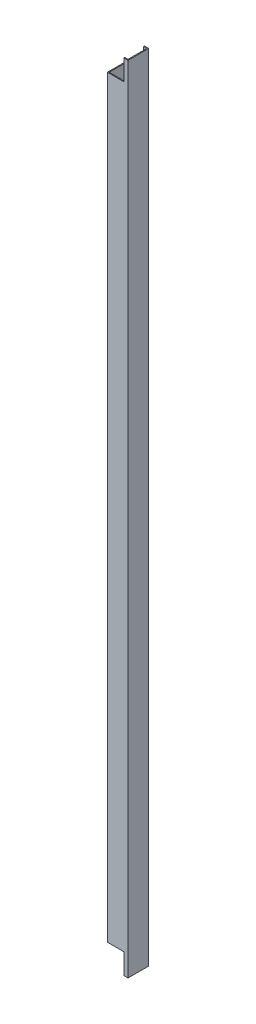
SolidWorks part; units mm, degrees
ref_plane "Front Plane" through (0, 0, 0) normal (0, 0, 1) x (1, 0, 0)
ref_plane "Top Plane" through (0, 0, 0) normal (0, 1, 0) x (1, 0, 0)
ref_plane "Right Plane" through (0, 0, 0) normal (1, 0, 0) x (0, 0, -1)
sketch "Sketch1" plane through (0, 0, 0) normal (0, 1, 0) x (1, 0, 0)
  line L0 (0, 0) -> (0, 50)
  line L1 (0, 50) -> (50, 50)
  line L2 (50, 50) -> (50, 0)
  line L3 (50, 0) -> (0, 0)
  line L4 (2.2, 47.8) -> (47.8, 47.8)
  line L5 (47.8, 47.8) -> (47.8, 2.2)
  line L6 (47.8, 2.2) -> (2.2, 2.2)
  line L7 (2.2, 2.2) -> (2.2, 47.8)
  dimension "D1" = 50
  dimension "D2" = 50
  dimension "D3" = 2.2
extrude "Boss-Extrude1" add sketch "Sketch1" along normal blind 1923
sketch "Sketch2" plane through (0, 0, 0) normal (0, 0, 1) x (1, 0, 0)
  line L0 (0, 0) -> (0, 50)
  line L1 (0, 1923) -> (0, 0) construction
  line L2 (0, 50) -> (40, 50)
  line L3 (40, 50) -> (40, 0)
  line L5 (40, 0) -> (0, 0)
  line L6 (0, 1923) -> (40, 1923)
  line L7 (0, 1923) -> (50, 1923) construction
  line L8 (40, 1923) -> (40, 1873)
  line L9 (40, 1873) -> (0, 1873)
  line L10 (0, 1873) -> (0, 1923)
  dimension "D1" = 50
  dimension "D2" = 40
  dimension "D3" = 50
  dimension "D4" = 40
extrude "Cut-Extrude2" cut sketch "Sketch2" against normal blind 50
equation "\"SquareTube_length\"=1923.0"
equation "\"D1@Boss-Extrude1\"=\"SquareTube_length\""
equation "\"SquareTube_inBack1_cutDepth50_R\"=50"
equation "\"D1@Sketch2\" = \"SquareTube_inBack5_cutDepth50_R\""
equation "\"SquareTube_inBack1_cutDepth50_L\"=50"
equation "\"D3@Sketch2\" = \"SquareTube_inBack5_cutDepth50_L\""
equation "\"CarBeamWidth\"=700.0"
equation "\"MetalSheet_3mm_length\"=5030.0"
equation "\"MetalSheet_3mm_width\"=1923.0"
equation "\"MetalSheet_3mm_FloorCut_L_length\"=1764.0"
equation "\"MetalSheet_3mm_FloorCut_L_disdance\"=1665.0"
equation "\"MetalSheet_3mm_FloorCut_R_length\"=1764.0"
equation "\"MetalSheet_3mm_FloorCut_R_disdance\"=1665.0"
equation "\"indoorHeight\"=1940.0"
equation "\"x\"=66.0"
equation "\"da\"=62.0"
equation "\"SquareTube_wheel_length\"= 750"
equation "\"channelSteel_length\"=5030.0"
equation "\"SquareTube_inFront1_cutDepth50_R\"=0.5"
equation "\"SquareTube_inFront1_cutDepth50_L\"=0.5"
equation "\"SquareTube_inFront2_cutDepth50_R\"=0.5"
equation "\"SquareTube_inFront2_cutDepth50_L\"=0.5"
equation "\"SquareTube_inFront3_cutDepth50_R\"=0.5"
equation "\"SquareTube_inFront3_cutDepth50_L\"=0.5"
equation "\"SquareTube_inFront4_cutDepth50_R\"=0.5"
equation "\"SquareTube_inFront4_cutDepth50_L\"=0.5"
equation "\"SquareTube_inFront5_cutDepth50_R\"=50"
equation "\"SquareTube_inFront5_cutDepth50_L\"=50"
equation "\"SquareTube_inFront6_cutDepth50_R\"=50"
equation "\"SquareTube_inFront6_cutDepth50_L\"=50"
equation "\"SquareTube_inFront7_cutDepth50_R\"=50"
equation "\"SquareTube_inFront7_cutDepth50_L\"=50"
equation "\"SquareTube_inFront8_cutDepth50_R\"=50"
equation "\"SquareTube_inFront8_cutDepth50_L\"=50"
equation "\"SquareTube_inFront9_cutDepth50_R\"=50"
equation "\"SquareTube_inFront9_cutDepth50_L\"=50"
equation "\"SquareTube_inFront10_cutDepth50_R\"=50"
equation "\"SquareTube_inFront10_cutDepth50_L\"=50"
equation "\"SquareTube_inBack2_cutDepth50_R\"=50"
equation "\"SquareTube_inBack2_cutDepth50_L\"=50"
equation "\"SquareTube_inBack3_cutDepth50_R\"=50"
equation "\"SquareTube_inBack3_cutDepth50_L\"=50"
equation "\"SquareTube_inBack4_cutDepth50_R\"=50"
equation "\"SquareTube_inBack4_cutDepth50_L\"=50"
equation "\"SquareTube_inBack5_cutDepth50_R\"=50"
equation "\"SquareTube_inBack5_cutDepth50_L\"=50"
equation "\"SquareTube_inBack6_cutDepth50_R\"=0.5"
equation "\"SquareTube_inBack6_cutDepth50_L\"=0.5"
equation "\"SquareTube_inFront11_cutDepth50_R\"=50"
equation "\"SquareTube_inFront11_cutDepth50_L\"=50"
equation "\"SquareTube_inFront12_cutDepth50_R\"=50"
equation "\"SquareTube_inFront12_cutDepth50_L\"=50"
equation "\"SquareTube_inFront13_cutDepth50_R\"=50"
equation "\"SquareTube_inFront13_cutDepth50_L\"=50"
equation "\"SquareTube_inFront14_cutDepth50_R\"=50"
equation "\"SquareTube_inFront14_cutDepth50_L\"=50"
equation "\"SquareTube_inBack7_cutDepth50_R\"=0.5"
equation "\"SquareTube_inBack7_cutDepth50_L\"=0.5"
equation "\"SquareTube_inBack8_cutDepth50_R\"=0.5"
equation "\"SquareTube_inBack8_cutDepth50_L\"=0.5"
